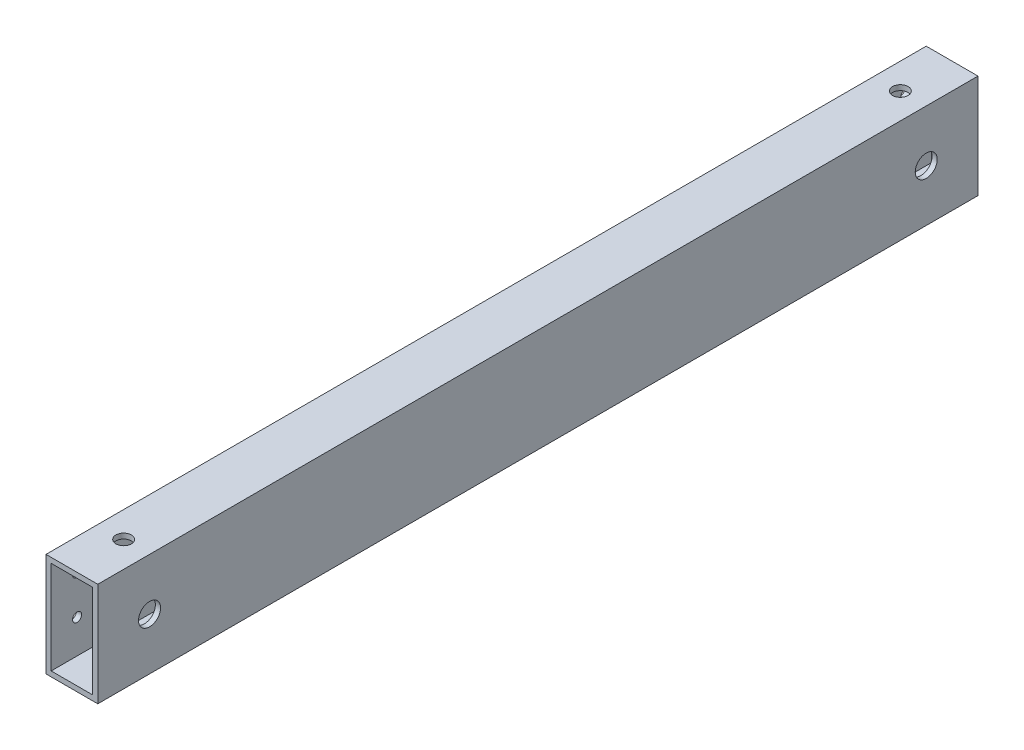
SolidWorks part; units mm, degrees
ref_plane "Plano frontal" through (0, 0, 0) normal (0, 0, 1) x (1, 0, 0)
ref_plane "Plano superior" through (0, 0, 0) normal (0, 1, 0) x (1, 0, 0)
ref_plane "Plano direito" through (0, 0, 0) normal (1, 0, 0) x (0, 0, -1)
sketch "Esboço1" plane through (0, 0, 0) normal (0, 0, 1) x (1, 0, 0)
  line L2 (0, 0) -> (20, 0)
  line L3 (0, 0) -> (0, 40)
  line L4 (0, 40) -> (20, 40)
  line L5 (20, 0) -> (20, 40)
  line L7 (2, 2) -> (18, 2)
  line L8 (2, 2) -> (2, 38)
  line L9 (2, 38) -> (18, 38)
  line L10 (18, 2) -> (18, 38)
  dimension "D1" = 40
  dimension "D2" = 20
  dimension "D3" = 2
  dimension "D4" = 2
  dimension "D5" = 2
  dimension "D6" = 2
extrude "Ressalto-extrusão1" add sketch "Esboço1" along normal blind 340
sketch "Esboço2" plane through (0, 0, 0) normal (-1, 0, 0) x (0, 0, 1)
  line L0 (0, 40) -> (0, 0) construction
  line L1 (340, 0) -> (0, 0) construction
  line L2 (170, 40) -> (170, 0) construction
  line L3 (340, 40) -> (0, 40) construction
  circle A0 centre (10, 30) radius 1.75
  circle A1 centre (10, 15) radius 1.75
  circle A2 centre (70, 15) radius 1.75
  circle A3 centre (55, 15) radius 1.75
  circle A4 centre (270, 15) radius 1.75
  circle A5 centre (285, 15) radius 1.75
  circle A6 centre (330, 15) radius 1.75
  circle A7 centre (330, 30) radius 1.75
  dimension "D1" = 3.5
  dimension "D2" = 3.5
  dimension "D7" = 3.5
  dimension "D8" = 3.5
  dimension "D3" = 10
  dimension "D4" = 15
  dimension "D5" = 15
  dimension "D6" = 10
  dimension "D9" = 70
  dimension "D10" = 15
extrude "Corte-extrusão1" cut sketch "Esboço2" against normal blind 2
sketch "Esboço3" plane through (0, 40, 0) normal (0, 1, 0) x (1, 0, 0)
  line L0 (20, -340) -> (0, -340) construction
  line L2 (20, -340) -> (20, 0) construction
  line L3 (20, -170) -> (0, -170) construction
  line L4 (0, -340) -> (0, 0) construction
  circle A0 centre (10, -320) radius 3
  circle A1 centre (10, -20) radius 3
  dimension "D1" = 6
  dimension "D2" = 20
  dimension "D3" = 10
extrude "Corte-extrusão2" cut sketch "Esboço3" against normal blind 2
sketch "Esboço4" plane through (20, 0, 0) normal (1, 0, 0) x (0, 0, -1)
  line L0 (-340, 40) -> (0, 40) construction
  line L2 (-340, 0) -> (-340, 40) construction
  line L3 (-170, 40) -> (-170, 0) construction
  line L4 (-340, 0) -> (0, 0) construction
  circle A0 centre (-320, 20) radius 4.25
  circle A1 centre (-20, 20) radius 4.25
  circle A2 centre (-320, 20) radius 4.25 construction
  point P13 (0, 0)
  dimension "D1" = 8.5
  dimension "D2" = 20
  dimension "D3" = 20
extrude "Corte-extrusão3" cut sketch "Esboço4" against normal blind 2
